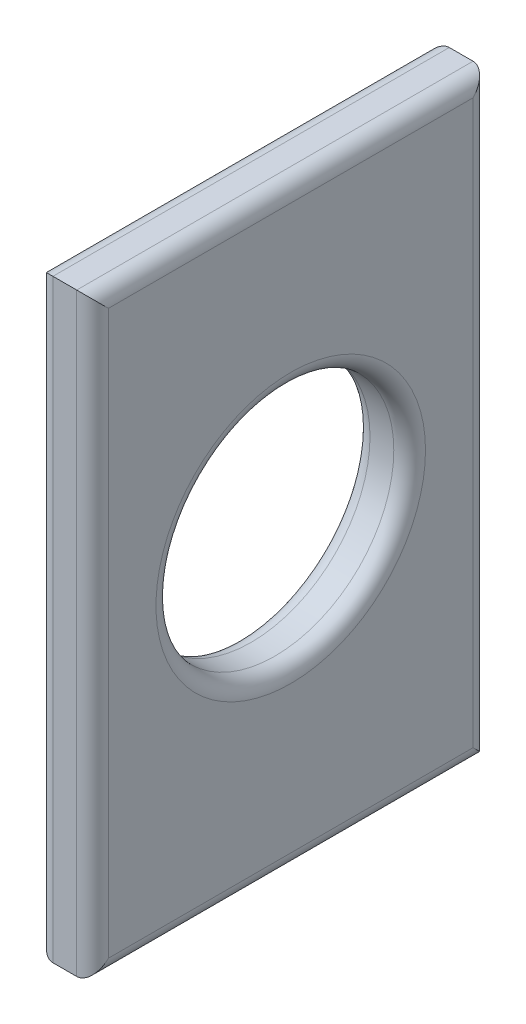
SolidWorks part; units mm, degrees
material "AISI 316 Stainless Steel Sheet (SS)"
ref_plane "Front Plane" through (0, 0, 0) normal (0, 0, 1) x (1, 0, 0)
ref_plane "Top Plane" through (0, 0, 0) normal (0, 1, 0) x (1, 0, 0)
ref_plane "Right Plane" through (0, 0, 0) normal (1, 0, 0) x (0, 0, -1)
sketch "Sketch1" plane through (0, 0, 0) normal (1, 0, 0) x (0, 0, -1)
  line L1 (-6.35, 9.525) -> (6.35, 9.525)
  line L2 (-6.35, 9.525) -> (-6.35, -9.525)
  line L3 (-6.35, -9.525) -> (6.35, -9.525)
  line L4 (6.35, 9.525) -> (6.35, -9.525)
  line L5 (-6.35, 9.525) -> (6.35, -9.525) construction
  line L6 (-6.35, -9.525) -> (6.35, 9.525) construction
  circle A0 centre (0, 0) radius 3.81
  point P0 (0, 0)
  dimension "D3" = 7.62
  dimension "D1" = 12.7
  dimension "D2" = 19.05
extrude "Boss-Extrude1" add sketch "Sketch1" along normal blind 1.778
fillet "Fillet1" radius 0.508 10 edges at (0, 0, -3.81) (0, 9.525, 0) (0, 0, 6.35) (0, -9.525, 0) (0, 0, -6.35) (1.778, 0, -3.81) (1.778, -9.525, 0) (1.778, 0, 6.35) (1.778, 9.525, 0) (1.778, 0, -6.35)
